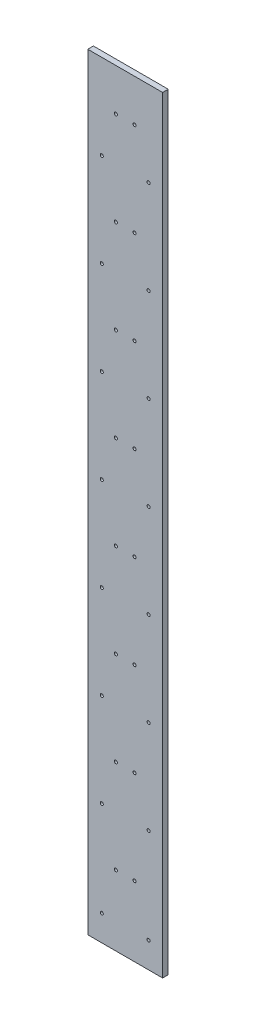
SolidWorks part; units mm, degrees
material "6061 合金"
ref_plane "前视基准面" through (0, 0, 0) normal (0, 0, 1) x (1, 0, 0)
ref_plane "上视基准面" through (0, 0, 0) normal (0, 1, 0) x (1, 0, 0)
ref_plane "右视基准面" through (0, 0, 0) normal (1, 0, 0) x (0, 0, -1)
other "Configuration Table"
sketch "Sketch1" plane through (0, 0, 0) normal (0, 0, 1) x (1, 0, 0)
  line L1 (-80, 0) -> (80, 0)
  line L2 (-80, 0) -> (-80, 1640)
  line L3 (-80, 1640) -> (80, 1640)
  line L4 (80, 0) -> (80, 1640)
extrude "Boss-Extrude1" add sketch "Sketch1" along normal blind 12
sketch "Sketch2" plane through (0, 0, 0) normal (0, 0, 1) x (1, 0, 0)
  circle A0 centre (-50, 55) radius 3.3
  circle A1 centre (-50, 258) radius 3.3
  circle A2 centre (-50, 458) radius 3.3
  circle A3 centre (-50, 658) radius 3.3
  circle A4 centre (-50, 858) radius 3.3
  circle A5 centre (-50, 1058) radius 3.3
  circle A6 centre (-50, 1258) radius 3.3
  circle A7 centre (-50, 1458) radius 3.3
  circle A8 centre (50, 55) radius 3.3
  circle A9 centre (50, 258) radius 3.3
  circle A10 centre (50, 458) radius 3.3
  circle A11 centre (50, 658) radius 3.3
  circle A12 centre (50, 858) radius 3.3
  circle A13 centre (50, 1058) radius 3.3
  circle A14 centre (50, 1258) radius 3.3
  circle A15 centre (50, 1458) radius 3.3
extrude "Cut-Extrude1" cut sketch "Sketch2" against normal through all and the other way through all
sketch "Sketch3" plane through (0, 0, 0) normal (0, 0, 1) x (1, 0, 0)
  circle A0 centre (-20, 150) radius 3.3
  circle A1 centre (-20, 350) radius 3.3
  circle A2 centre (-20, 550) radius 3.3
  circle A3 centre (-20, 750) radius 3.3
  circle A4 centre (-20, 950) radius 3.3
  circle A5 centre (-20, 1150) radius 3.3
  circle A6 centre (-20, 1350) radius 3.3
  circle A7 centre (-20, 1550) radius 3.3
  circle A8 centre (20, 150) radius 3.3
  circle A9 centre (20, 350) radius 3.3
  circle A10 centre (20, 550) radius 3.3
  circle A11 centre (20, 750) radius 3.3
  circle A12 centre (20, 950) radius 3.3
  circle A13 centre (20, 1150) radius 3.3
  circle A14 centre (20, 1350) radius 3.3
  circle A15 centre (20, 1550) radius 3.3
extrude "Cut-Extrude2" cut sketch "Sketch3" against normal through all and the other way through all
sketch "Sketch4" plane through (0, 0, 0) normal (0, 0, 1) x (1, 0, 0)
  circle A0 centre (-20, 150) radius 5.5
  circle A1 centre (-20, 350) radius 5.5
  circle A2 centre (-20, 550) radius 5.5
  circle A3 centre (-20, 750) radius 5.5
  circle A4 centre (-20, 950) radius 5.5
  circle A5 centre (-20, 1150) radius 5.5
  circle A6 centre (-20, 1350) radius 5.5
  circle A7 centre (-20, 1550) radius 5.5
  circle A8 centre (20, 150) radius 5.5
  circle A9 centre (20, 350) radius 5.5
  circle A10 centre (20, 550) radius 5.5
  circle A11 centre (20, 750) radius 5.5
  circle A12 centre (20, 950) radius 5.5
  circle A13 centre (20, 1150) radius 5.5
  circle A14 centre (20, 1350) radius 5.5
  circle A15 centre (20, 1550) radius 5.5
extrude "Cut-Extrude4" cut sketch "Sketch4" along normal blind 6.5
